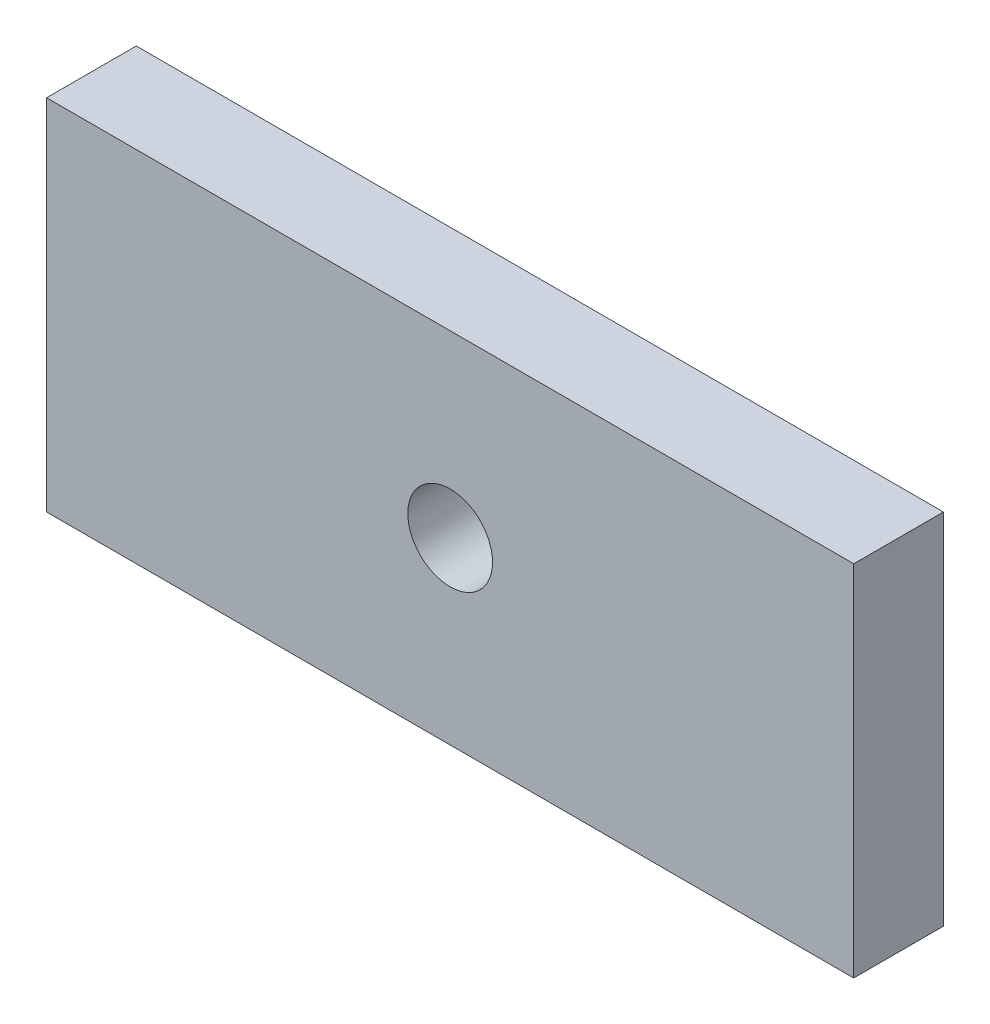
SolidWorks part; units mm, degrees
ref_plane "Front Plane" through (0, 0, 0) normal (0, 0, 1) x (1, 0, 0)
ref_plane "Top Plane" through (0, 0, 0) normal (0, 1, 0) x (1, 0, 0)
ref_plane "Right Plane" through (0, 0, 0) normal (1, 0, 0) x (0, 0, -1)
sketch "Sketch1" plane through (0, 0, 0) normal (0, 0, 1) x (1, 0, 0)
  line L1 (0, 0) -> (114.3, 0)
  line L2 (0, 0) -> (0, 50.8)
  line L3 (0, 50.8) -> (114.3, 50.8)
  line L4 (114.3, 0) -> (114.3, 50.8)
  circle A0 centre (57.15, 25.4) radius 6
  point P9 (17.6835, 35.0944)
  dimension "D3" = 12
  dimension "D1" = 114.3
  dimension "D2" = 50.8
  dimension "D4" = 25.4
  dimension "D5" = 57.15
extrude "Boss-Extrude1" add sketch "Sketch1" along normal blind 12.7
